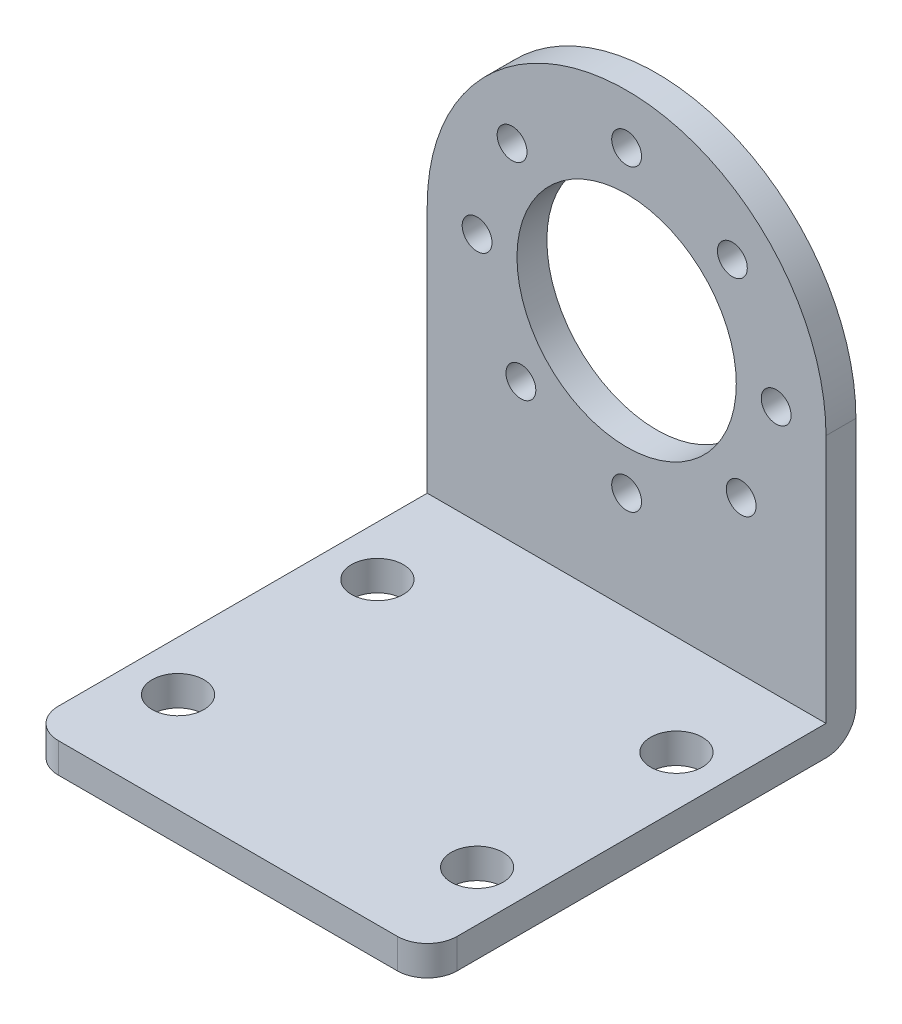
SolidWorks part; units mm, degrees
ref_plane "前视基准面" through (0, 0, 0) normal (0, 0, 1) x (1, 0, 0)
ref_plane "上视基准面" through (0, 0, 0) normal (0, 1, 0) x (1, 0, 0)
ref_plane "右视基准面" through (0, 0, 0) normal (1, 0, 0) x (0, 0, -1)
other "Configuration Table"
sketch "草图1" plane through (0, 0, 0) normal (0, 0, 1) x (1, 0, 0)
  line L0 (0, -22.1706) -> (0, 22.1706) construction
  line L1 (-26.7277, 0) -> (26.7277, 0) construction
  line L2 (-21.2985, 17.8715) -> (21.2985, -17.8715) construction
  line L3 (-18.6614, -18.6614) -> (18.6614, 18.6614) construction
  line L5 (-20, 0) -> (20, 0)
  line L6 (-20, 0) -> (-20, -28)
  line L7 (-20, -28) -> (20, -28)
  line L8 (20, 0) -> (20, -28)
  circle A0 centre (0, 0) radius 15
  circle A1 centre (0, 15) radius 1.4974
  circle A2 centre (10.6066, 10.6066) radius 1.4974
  circle A3 centre (15, 0) radius 1.4974
  circle A4 centre (-11.4907, 9.6418) radius 1.4974
  circle A5 centre (-15, 0) radius 1.4974
  circle A6 centre (-10.6066, -10.6066) radius 1.4974
  circle A7 centre (0, -15) radius 1.4974
  circle A8 centre (11.4907, -9.6418) radius 1.4974
  circle A9 centre (0, 0) radius 20
  circle A10 centre (0, 0) radius 11
  point P6 (0, 0)
  point P9 (0, 0)
  point P12 (0, 0)
  point P15 (0, 0)
  dimension "D1" = 28
  dimension "D2" = 40
extrude "凸台-拉伸1" add sketch "草图1" along normal blind 3 contours A10 L5 A3 A0 A2 A1 A4 A5 | A10 L5 A5 A0 A6 A7 A8 A3 | L5 A9 A5 A0 A4 A1 A2 A3 | L5 A9 A3 A0 A8 A7 A6 A5 | A9 L6 L7 L8
sketch "草图2" plane through (0, 0, 3) normal (0, 0, 1) x (1, 0, 0)
  line L0 (20, 0) -> (20, -28) construction
  line L1 (-20, -28) -> (20, -28)
  line L2 (-20, -28) -> (-20, -25)
  line L3 (-20, -25) -> (20, -25)
  line L4 (20, -28) -> (20, -25)
extrude "凸台-拉伸2" add sketch "草图2" along normal blind 40 contours L2 L1 L4 L3
sketch "草图3" plane through (0, -25, 0) normal (0, 1, 0) x (1, 0, 0)
  line L0 (-60, 37) -> (20, -43) construction
  line L3 (-20, -43) -> (35335.3391, 35312.3391) construction
  line L4 (0, -50.0657) -> (0, 4.0657) construction
  line L5 (0, -23) -> (50000, -23) construction
  circle A0 centre (-15, -13) radius 2.6
  circle A2 centre (-15, -33) radius 2.6
  circle A3 centre (15, -33) radius 2.6
  circle A4 centre (15, -13) radius 2.6
  point P4 (-20, -3)
  point P14 (0, -23)
  dimension "D1" = 20
extrude "切除-拉伸1" cut sketch "草图3" against normal blind 40
fillet "圆角1" radius 3 3 edges at (20, -26.5, 43) (-20, -26.5, 43) (0, -28, 0)
